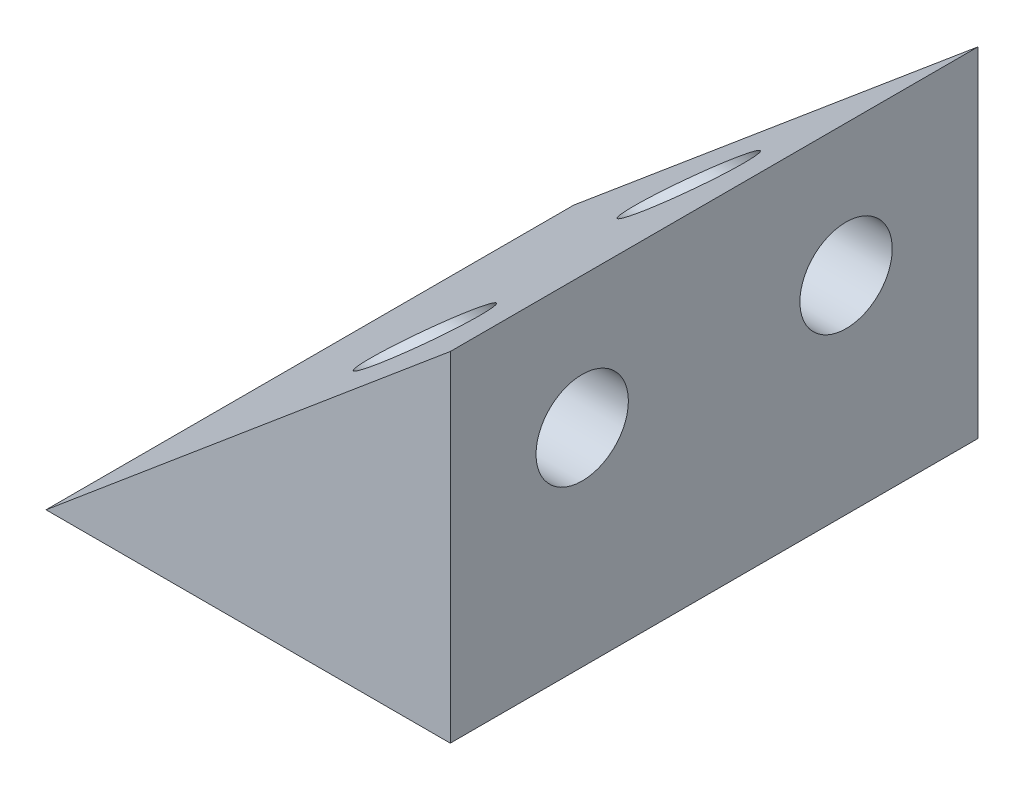
SolidWorks part; units mm, degrees
ref_plane "Front Plane" through (0, 0, 0) normal (0, 0, 1) x (1, 0, 0)
ref_plane "Top Plane" through (0, 0, 0) normal (0, 1, 0) x (1, 0, 0)
ref_plane "Right Plane" through (0, 0, 0) normal (1, 0, 0) x (0, 0, -1)
sketch "Sketch1" plane through (0, 0, 0) normal (0, 0, 1) x (1, 0, 0)
  line L0 (0, 0) -> (-15.3209, 0)
  line L1 (-15.3209, 0) -> (0, 12.8558)
  line L2 (0, 12.8558) -> (0, 0)
  dimension "D1" = 20
  dimension "D2" = 40
extrude "Boss-Extrude1" add sketch "Sketch1" along normal blind 20
sketch "Sketch2" plane through (-6.3302, 7.5441, 0) normal (-0.6428, 0.766, 0) x (0, 0, 1)
  line L0 (20, 8.2635) -> (0, 8.2635) construction
  line L1 (20, 8.2635) -> (20, -11.7365) construction
  line L2 (0, -1.7365) -> (20, -1.7365) construction
  line L3 (0, 8.2635) -> (0, -11.7365) construction
  line L4 (10, 8.2635) -> (10, -11.7365) construction
  line L5 (20, -11.7365) -> (0, -11.7365) construction
sketch "Sketch3" plane through (0, 0, 0) normal (1, 0, 0) x (0, 0, -1)
  line L0 (-10, 12.8558) -> (-10, 0) construction
  line L1 (-20, 12.8558) -> (0, 12.8558) construction
  line L3 (-20, 6.4279) -> (0, 6.4279) construction
  line L4 (0, 0) -> (0, 12.8558) construction
  circle A1 centre (-5, 7.8558) radius 1.75
  circle A2 centre (-15, 7.8558) radius 1.75
  dimension "D1" = 3.5
  dimension "D2" = 5
  dimension "D3" = 5
extrude "Cut-Extrude1" cut sketch "Sketch3" along direction (-1, 0, 0) on the side against the normal up to surface (3.8732 mm away)
sketch "Sketch4" plane through (0, 0, 0) normal (0, -1, 0) x (1, 0, 0)
  line L0 (-7.6604, 0) -> (-7.6604, 20) construction
  line L1 (-15.3209, 0) -> (0, 0) construction
  line L2 (-15.3209, 20) -> (0, 20) construction
  text T0 "40\r\n\r\n" font "Century Gothic" height 3.5
extrude "Cut-Extrude2" cut sketch "Sketch4" against normal blind 1
